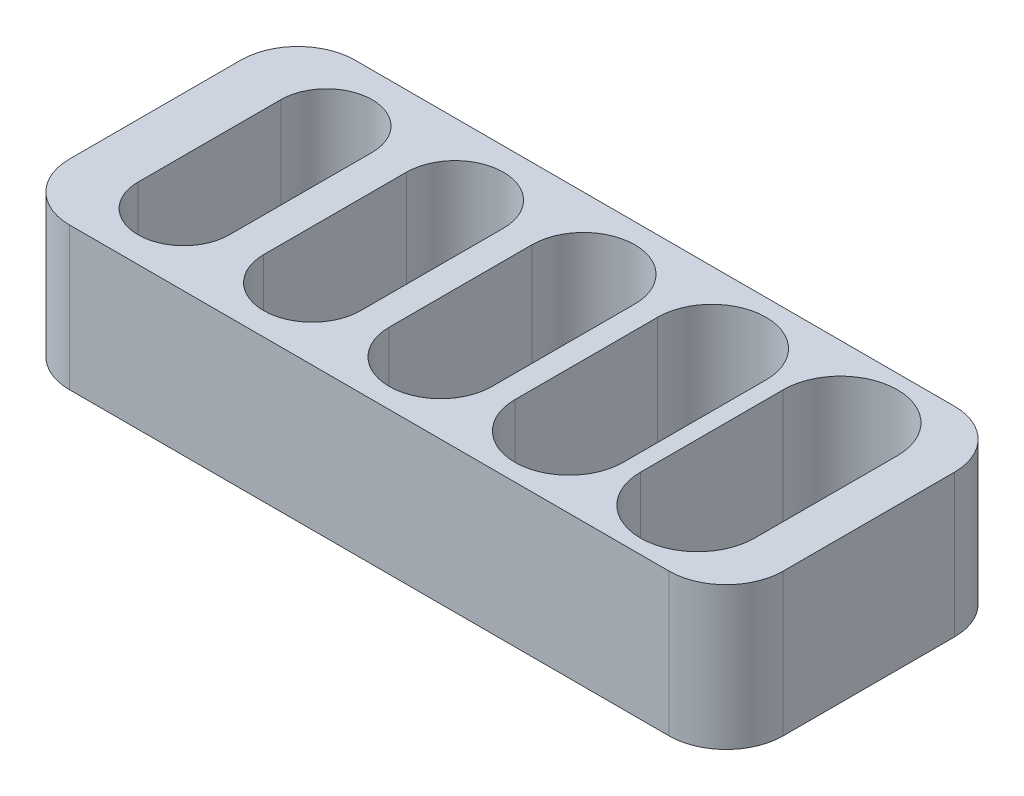
SolidWorks part; units mm, degrees
ref_plane "Front Plane" through (0, 0, 0) normal (0, 0, 1) x (1, 0, 0)
ref_plane "Top Plane" through (0, 0, 0) normal (0, 1, 0) x (1, 0, 0)
ref_plane "Right Plane" through (0, 0, 0) normal (1, 0, 0) x (0, 0, -1)
sketch "Sketch1" plane through (0, 0, 0) normal (0, 1, 0) x (1, 0, 0)
  line L0 (0, 0) -> (0, 5) construction
  line L1 (12.5, -5) -> (-12.5, -5)
  line L2 (12.5, -5) -> (12.5, 5)
  line L3 (12.5, 5) -> (-12.5, 5)
  line L4 (-12.5, -5) -> (-12.5, 5)
  line L5 (12.5, -5) -> (-12.5, 5) construction
  line L6 (12.5, 5) -> (-12.5, -5) construction
  line L7 (0, -2.5) -> (0, 2.5) construction
  line L8 (-1.8, -2.5) -> (-1.8, 2.5)
  line L9 (1.8, -2.5) -> (1.8, 2.5)
  line L10 (-4.5, -2.5) -> (-4.5, 2.5) construction
  line L11 (-6.2, -2.5) -> (-6.2, 2.5)
  line L12 (-2.8, -2.5) -> (-2.8, 2.5)
  line L13 (4.5, -2.5) -> (4.5, 2.5) construction
  line L16 (-9, -2.5) -> (-9, 2.5) construction
  line L17 (-10.6, -2.5) -> (-10.6, 2.5)
  line L18 (-7.4, -2.5) -> (-7.4, 2.5)
  line L19 (2.6, -2.5) -> (2.6, 2.5)
  line L20 (6.4, -2.5) -> (6.4, 2.5)
  line L21 (9, -2.5) -> (9, 2.5) construction
  line L22 (7, -2.5) -> (7, 2.5)
  line L23 (11, -2.5) -> (11, 2.5)
  line L24 (-9, 0) -> (-4.5, 0) construction
  line L25 (-4.5, 0) -> (0, 0) construction
  line L26 (0, 0) -> (4.5, 0) construction
  line L27 (4.5, 0) -> (9, 0) construction
  arc A0 (-1.8, -2.5) -> (1.8, -2.5) centre (0, -2.5) ccw
  arc A1 (1.8, 2.5) -> (-1.8, 2.5) centre (0, 2.5) ccw
  arc A2 (-6.2, -2.5) -> (-2.8, -2.5) centre (-4.5, -2.5) ccw
  arc A3 (-2.8, 2.5) -> (-6.2, 2.5) centre (-4.5, 2.5) ccw
  arc A6 (-10.6, -2.5) -> (-7.4, -2.5) centre (-9, -2.5) ccw
  arc A7 (-7.4, 2.5) -> (-10.6, 2.5) centre (-9, 2.5) ccw
  arc A8 (2.6, -2.5) -> (6.4, -2.5) centre (4.5, -2.5) ccw
  arc A9 (6.4, 2.5) -> (2.6, 2.5) centre (4.5, 2.5) ccw
  arc A10 (7, -2.5) -> (11, -2.5) centre (9, -2.5) ccw
  arc A11 (11, 2.5) -> (7, 2.5) centre (9, 2.5) ccw
  point P0 (0, 0)
  point P10 (0, 0)
  point P17 (-4.5, 0)
  point P23 (-9, 2.5)
  point P26 (4.5, 0)
  point P32 (-9, 0)
  point P41 (9, 0)
  point P46 (0, 0)
  dimension "D4" = 1.8
  dimension "D5" = 1.6
  dimension "D6" = 1.7
  dimension "D8" = 1.9
  dimension "D9" = 2
  dimension "D1" = 10
  dimension "D2" = 25
  dimension "D3" = 5
  dimension "D7" = 4.5
extrude "Boss-Extrude1" add sketch "Sketch1" along normal blind 5
fillet "Fillet1" radius 2 4 edges at (12.5, 2.5, -5) (12.5, 2.5, 5) (-12.5, 2.5, 5) (-12.5, 2.5, -5)
